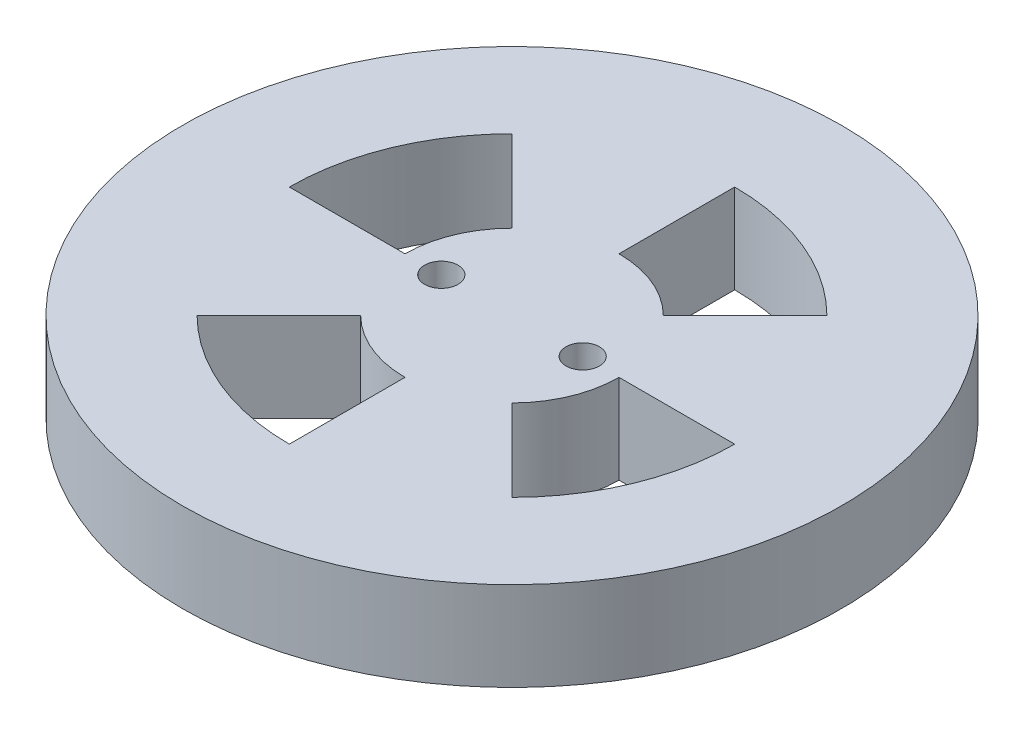
SolidWorks part; units mm, degrees
ref_plane "Plano frontal" through (0, 0, 0) normal (0, 0, 1) x (1, 0, 0)
ref_plane "Plano superior" through (0, 0, 0) normal (0, 1, 0) x (1, 0, 0)
ref_plane "Plano direito" through (0, 0, 0) normal (1, 0, 0) x (0, 0, -1)
sketch "Esboço1" plane through (0, 0, 0) normal (0, 1, 0) x (1, 0, 0)
  circle A0 centre (-36.4415, 11.938) radius 29.6
extrude "Ressalto-extrusão1" add sketch "Esboço1" along normal blind 8
sketch "Esboço2" plane through (0, 8, 0) normal (0, 1, 0) x (1, 0, 0)
  line L0 (-26.8305, 11.938) -> (-16.4415, 11.938)
  line L1 (-36.4415, 21.549) -> (-36.4415, 31.938)
  line L2 (-46.0525, 11.938) -> (-56.4415, 11.938)
  line L3 (-36.4415, 2.327) -> (-36.4415, -8.062)
  line L4 (-43.2375, 5.142) -> (-50.5836, -2.2042)
  line L5 (-43.2375, 18.734) -> (-50.5836, 26.0801)
  line L6 (-29.6455, 18.734) -> (-22.2994, 26.0801)
  line L7 (-29.6455, 5.142) -> (-22.2994, -2.2042)
  circle A0 centre (-36.4415, 11.938) radius 20
  circle A1 centre (-36.4415, 11.938) radius 9.611
  dimension "D1" = 45
  dimension "D2" = 45
  dimension "D3" = 45
  dimension "D4" = 45
  dimension "D5" = 45
extrude "Corte-extrusão2" cut sketch "Esboço2" against normal blind 8 contours A1 L5 A0 L2 | A1 L6 A0 L1 | A1 L7 A0 L0 | A1 L4 A0 L3
sketch "Esboço4" plane through (0, 8, 0) normal (0, 1, 0) x (1, 0, 0)
  line L0 (-36.4415, 11.938) -> (-30.0915, 11.938) construction
  line L1 (-36.4415, 11.938) -> (-42.7915, 11.938) construction
  circle A0 centre (-30.0915, 11.938) radius 1.5
  circle A1 centre (-42.7915, 11.938) radius 1.5
extrude "Corte-extrusão4" cut sketch "Esboço4" against normal blind 8
